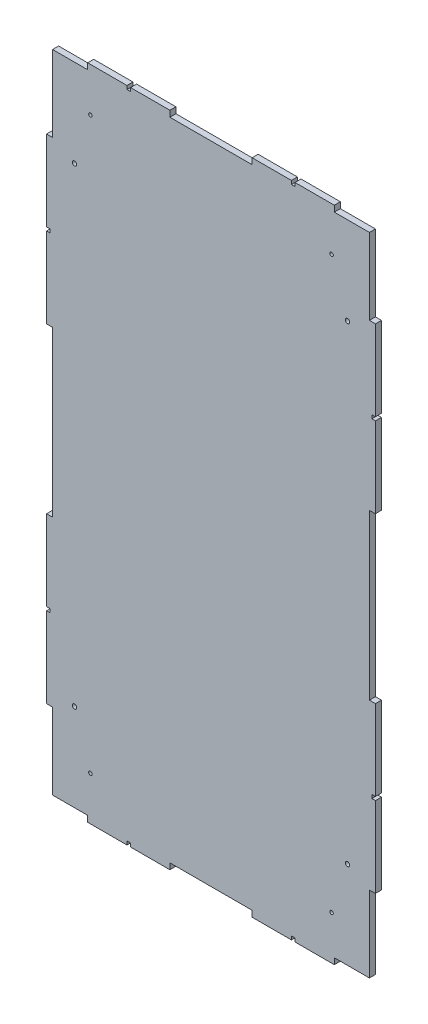
SolidWorks part; units mm, degrees
ref_plane "Front Plane" through (0, 0, 0) normal (0, 0, 1) x (1, 0, 0)
ref_plane "Top Plane" through (0, 0, 0) normal (0, 1, 0) x (1, 0, 0)
ref_plane "Right Plane" through (0, 0, 0) normal (1, 0, 0) x (0, 0, -1)
sketch "Sketch1" plane through (0, 0, 0) normal (0, 0, 1) x (1, 0, 0)
  line L0 (-0.0027, 588.9972) -> (-0.0027, 519.4972)
  line L1 (-0.0027, 519.4972) -> (-5.5027, 519.4972)
  line L2 (-5.5027, 519.4972) -> (-5.5027, 446.1222)
  line L3 (-5.5027, 446.1222) -> (-2.2527, 446.1222)
  line L4 (-2.2527, 446.1222) -> (-2.2527, 444.4972)
  line L5 (-2.2527, 444.4972) -> (-2.2527, 442.8722)
  line L6 (-2.2527, 442.8722) -> (-5.5027, 442.8722)
  line L7 (-5.5027, 442.8722) -> (-5.5027, 369.4972)
  line L8 (-5.5027, 369.4972) -> (-0.0027, 369.4972)
  line L9 (-0.0027, 369.4972) -> (-0.0027, 219.4972)
  line L10 (-0.0027, 219.4972) -> (-5.5027, 219.4972)
  line L11 (-5.5027, 219.4972) -> (-5.5027, 146.1222)
  line L12 (-5.5027, 146.1222) -> (-2.2527, 146.1222)
  line L13 (-2.2527, 146.1222) -> (-2.2527, 144.4972)
  line L14 (-2.2527, 144.4972) -> (-2.2527, 142.8722)
  line L15 (-2.2527, 142.8722) -> (-5.5027, 142.8722)
  line L16 (-5.5027, 142.8722) -> (-5.5027, 69.4972)
  line L17 (-5.5027, 69.4972) -> (-0.0027, 69.4972)
  line L18 (-0.0027, 69.4972) -> (-0.0027, -0.0028)
  line L19 (-0.0027, -0.0028) -> (31.9973, -0.0028)
  line L20 (31.9973, -0.0028) -> (31.9973, -5.5028)
  line L21 (31.9973, -5.5028) -> (67.8723, -5.5028)
  line L22 (67.8723, -5.5028) -> (67.8723, -2.2528)
  line L23 (67.8723, -2.2528) -> (69.4973, -2.2528)
  line L24 (69.4973, -2.2528) -> (71.1223, -2.2528)
  line L25 (71.1223, -2.2528) -> (71.1223, -5.5028)
  line L26 (71.1223, -5.5028) -> (106.9973, -5.5028)
  line L27 (106.9973, -5.5028) -> (106.9973, -0.0028)
  line L28 (106.9973, -0.0028) -> (181.9973, -0.0028)
  line L29 (181.9973, -0.0028) -> (181.9973, -5.5028)
  line L30 (181.9973, -5.5028) -> (217.8723, -5.5028)
  line L31 (217.8723, -5.5028) -> (217.8723, -2.2528)
  line L32 (217.8723, -2.2528) -> (219.4973, -2.2528)
  line L33 (219.4973, -2.2528) -> (221.1223, -2.2528)
  line L34 (221.1223, -2.2528) -> (221.1223, -5.5028)
  line L35 (221.1223, -5.5028) -> (256.9973, -5.5028)
  line L36 (256.9973, -5.5028) -> (256.9973, -0.0028)
  line L37 (256.9973, -0.0028) -> (288.9973, -0.0028)
  line L38 (288.9973, -0.0028) -> (288.9973, 69.4972)
  line L39 (288.9973, 69.4972) -> (294.4973, 69.4972)
  line L40 (294.4973, 69.4972) -> (294.4973, 142.8722)
  line L41 (294.4973, 142.8722) -> (291.2473, 142.8722)
  line L42 (291.2473, 142.8722) -> (291.2473, 144.4972)
  line L43 (291.2473, 144.4972) -> (291.2473, 146.1222)
  line L44 (291.2473, 146.1222) -> (294.4973, 146.1222)
  line L45 (294.4973, 146.1222) -> (294.4973, 219.4972)
  line L46 (294.4973, 219.4972) -> (288.9973, 219.4972)
  line L47 (288.9973, 219.4972) -> (288.9973, 369.4972)
  line L48 (288.9973, 369.4972) -> (294.4973, 369.4972)
  line L49 (294.4973, 369.4972) -> (294.4973, 442.8722)
  line L50 (294.4973, 442.8722) -> (291.2473, 442.8722)
  line L51 (291.2473, 442.8722) -> (291.2473, 444.4972)
  line L52 (291.2473, 444.4972) -> (291.2473, 446.1222)
  line L53 (291.2473, 446.1222) -> (294.4973, 446.1222)
  line L54 (294.4973, 446.1222) -> (294.4973, 519.4972)
  line L55 (294.4973, 519.4972) -> (288.9973, 519.4972)
  line L56 (288.9973, 519.4972) -> (288.9973, 588.9972)
  line L57 (288.9973, 588.9972) -> (256.9973, 588.9972)
  line L58 (256.9973, 588.9972) -> (256.9973, 594.4972)
  line L59 (256.9973, 594.4972) -> (221.1223, 594.4972)
  line L60 (221.1223, 594.4972) -> (221.1223, 591.2472)
  line L61 (221.1223, 591.2472) -> (219.4973, 591.2472)
  line L62 (219.4973, 591.2472) -> (217.8723, 591.2472)
  line L63 (217.8723, 591.2472) -> (217.8723, 594.4972)
  line L64 (217.8723, 594.4972) -> (181.9973, 594.4972)
  line L65 (181.9973, 594.4972) -> (181.9973, 588.9972)
  line L66 (181.9973, 588.9972) -> (106.9973, 588.9972)
  line L67 (106.9973, 588.9972) -> (106.9973, 594.4972)
  line L68 (106.9973, 594.4972) -> (71.1223, 594.4972)
  line L69 (71.1223, 594.4972) -> (71.1223, 591.2472)
  line L70 (71.1223, 591.2472) -> (69.4973, 591.2472)
  line L71 (69.4973, 591.2472) -> (67.8723, 591.2472)
  line L72 (67.8723, 591.2472) -> (67.8723, 594.4972)
  line L73 (67.8723, 594.4972) -> (31.9973, 594.4972)
  line L74 (31.9973, 594.4972) -> (31.9973, 588.9972)
  line L75 (31.9973, 588.9972) -> (-0.0027, 588.9972)
sketch "Sketch2" plane through (0, 0, 0) normal (0, 0, 1) x (1, 0, 0)
  line L0 (181.9973, 588.9972) -> (106.9973, 588.9972) construction
  line L1 (19.9973, 508.9972) -> (268.9973, 508.9972)
  line L2 (19.9973, 508.9972) -> (19.9973, 79.9972)
  line L3 (19.9973, 79.9972) -> (268.9973, 79.9972)
  line L4 (268.9973, 508.9972) -> (268.9973, 79.9972)
  line L5 (-0.0027, 588.9972) -> (-0.0027, 519.4972) construction
  line L6 (-0.0027, 369.4972) -> (-0.0027, 219.4972) construction
  circle A0 centre (19.9973, 508.9972) radius 2
  circle A1 centre (268.9973, 508.9972) radius 2
  circle A2 centre (268.9973, 79.9972) radius 2
  circle A3 centre (19.9973, 79.9972) radius 2
  point P12 (144.4973, 508.9972)
  point P13 (144.4973, 588.9972)
  point P14 (19.9973, 294.4972)
  point P17 (-0.0027, 294.4972)
  dimension "D3" = 4
  dimension "D1" = 80
  dimension "D2" = 20
extrude "Boss-Extrude1" add sketch "Sketch1" along normal blind 5.5
extrude "Cut-Extrude1" cut sketch "Sketch2" against normal through all and the other way through all contours L4 A1 L1 | L1 A1 L4 | L2 A0 L1 | L1 A0 L2 | L2 A3 L3 | L3 A3 L2 | L3 A2 L4 | L4 A2 L3
sketch "Sketch3" plane through (0, 0, 5.5) normal (0, 0, 1) x (1, 0, 0)
  line L1 (34.4973, 554.4972) -> (254.4973, 554.4972)
  line L2 (34.4973, 554.4972) -> (34.4973, 34.4972)
  line L3 (34.4973, 34.4972) -> (254.4973, 34.4972)
  line L4 (254.4973, 554.4972) -> (254.4973, 34.4972)
  line L6 (-5.5027, 519.4972) -> (-5.5027, 446.1222) construction
  line L7 (294.4973, 446.1222) -> (294.4973, 519.4972) construction
  line L8 (217.8723, 594.4972) -> (181.9973, 594.4972) construction
  line L9 (181.9973, -5.5028) -> (217.8723, -5.5028) construction
  circle A0 centre (34.4973, 554.4972) radius 1.6
  circle A1 centre (254.4973, 554.4972) radius 1.6
  circle A2 centre (34.4973, 34.4972) radius 1.6
  circle A3 centre (254.4973, 34.4972) radius 1.6
  point P17 (0, 0)
  dimension "D5" = 3.2
  dimension "D1" = 40
  dimension "D2" = 40
  dimension "D3" = 40
  dimension "D4" = 40
extrude "Cut-Extrude2" cut sketch "Sketch3" against normal through all contours A0 | A1 | A2 | A3
